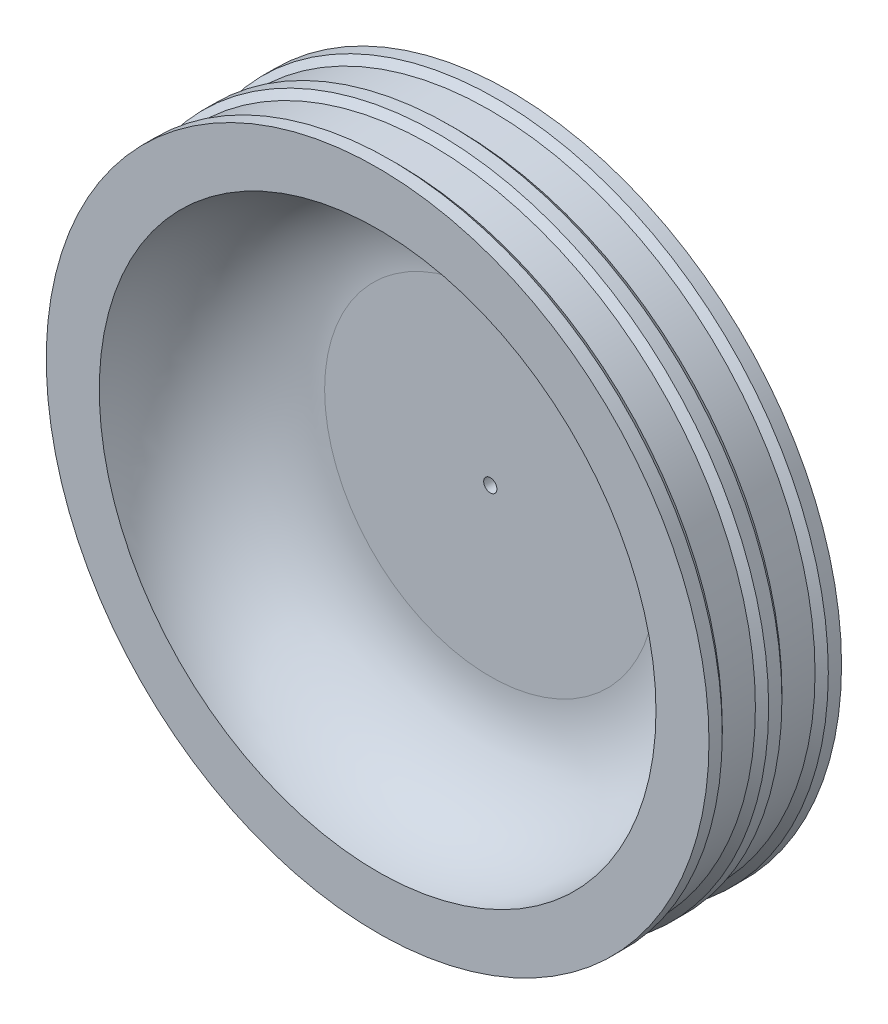
SolidWorks part; units mm, degrees
ref_plane "Front Plane" through (0, 0, 0) normal (0, 0, 1) x (1, 0, 0)
ref_plane "Top Plane" through (0, 0, 0) normal (0, 1, 0) x (1, 0, 0)
ref_plane "Right Plane" through (0, 0, 0) normal (1, 0, 0) x (0, 0, -1)
sketch "Sketch1" plane through (0, 0, 0) normal (0, 0, 1) x (1, 0, 0)
  circle A0 centre (0, 0) radius 50
  circle A1 centre (0, 0) radius 1
  dimension "D1" = 100
  dimension "D2" = 2
extrude "Boss-Extrude1" add sketch "Sketch1" along normal blind 20
sketch "Sketch2" plane through (0, 0, 0) normal (1, 0, 0) x (0, 0, -1)
  line L0 (-18, 50) -> (-17, 49)
  line L1 (0, 50) -> (-20, 50) construction
  line L2 (-17, 49) -> (-12, 49)
  line L3 (-12, 49) -> (-11, 50)
  line L4 (-10, -1000) -> (-10, 49000) construction
  line L5 (-9, 50) -> (-8, 49)
  line L6 (-8, 49) -> (-3, 49)
  line L7 (-3, 49) -> (-2, 50)
  line L8 (-18, 50) -> (-11, 50)
  line L9 (-9, 50) -> (-2, 50)
  line L11 (-20, 50) -> (-20, -50) construction
  line L12 (-1011.8585, 0) -> (48988.1415, 0) construction
  dimension "D1" = 7
  dimension "D2" = 7
  dimension "D3" = 5
  dimension "D4" = 5
  dimension "D5" = 1
  dimension "D6" = 10
  dimension "D7" = 2
revolve "Cut-Revolve1" cut sketch "Sketch2" angle 360 about L12
sketch "Sketch4" plane through (0, 0, 0) normal (1, 0, 0) x (0, 0, -1)
  line L0 (-9, -1000) -> (-9, 49000) construction
  line L1 (-9, 50) -> (-9, -50) construction
  line L2 (-20, 50) -> (-20, -50) construction
  line L3 (-3, 0) -> (-3, 25)
  line L4 (11, 0) -> (-11, 0) construction
  line L6 (-1013, 42) -> (48987, 42) construction
  line L7 (-20, 42) -> (-20, 0)
  line L8 (-20, 0) -> (-3, 0)
  line L9 (-1012, 0) -> (48988, 0) construction
  line L11 (-3, 49) -> (-3, -49) construction
  arc A0 (-3, 25) -> (-20, 42) centre (-20, 25) ccw
  point P5 (-9, 0)
  point P11 (-3, 29.7352)
  point P16 (-12, 36.4463)
  point P20 (0, 0)
  point P22 (-12, 36.2398)
  point P23 (0, 0)
  point P25 (-3, 0)
  dimension "D1" = 11
  dimension "D2" = 8
revolve "Cut-Revolve2" cut sketch "Sketch4" angle 360 about L9
